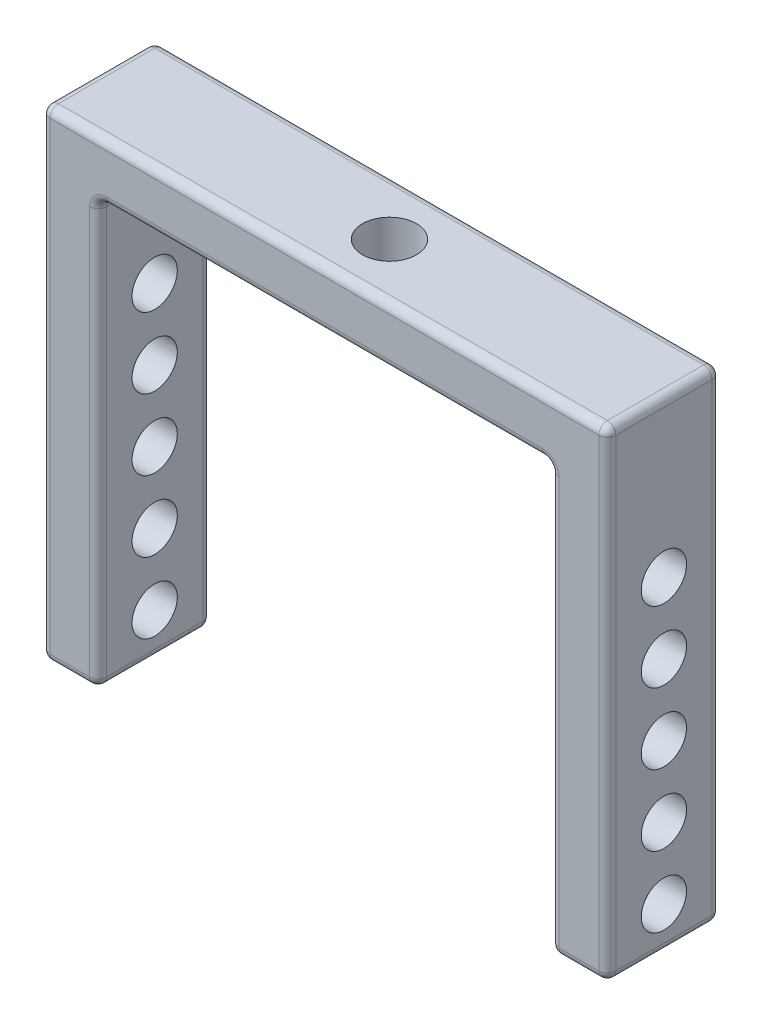
SolidWorks part; units mm, degrees
ref_plane "Alzado" through (0, 0, 0) normal (0, 0, 1) x (1, 0, 0)
ref_plane "Planta" through (0, 0, 0) normal (0, 1, 0) x (1, 0, 0)
ref_plane "Vista lateral" through (0, 0, 0) normal (1, 0, 0) x (0, 0, -1)
sketch "Sketch1" plane through (0, 0, 0) normal (0, 0, 1) x (1, 0, 0)
  line L0 (0, 0) -> (415, 0) construction
  line L1 (415, 0) -> (415, 270) construction
  line L2 (415, 270) -> (0, 270) construction
  line L3 (0, 270) -> (0, 0) construction
  line L4 (207.5, 270) -> (207.5, 0) construction
  line L6 (107.5, 210) -> (107.5, 60)
  line L7 (107.5, 60) -> (127.5, 60)
  line L8 (127.5, 210) -> (127.5, 60)
  line L9 (307.5, 230) -> (307.5, 210)
  line L10 (287.5, 210) -> (287.5, 60)
  line L11 (307.5, 230) -> (107.5, 230)
  line L12 (207.5, 230) -> (207.5, 210)
  line L13 (287.5, 210) -> (127.5, 210)
  line L14 (107.5, 230) -> (107.5, 210)
  line L15 (307.5, 60) -> (287.5, 60)
  line L16 (307.5, 210) -> (307.5, 60)
  point P3 (117.5, 135)
  point P13 (127.5, 135)
  point P14 (157.5, 220)
  dimension "D1" = 415
  dimension "D2" = 270
  dimension "D3" = 20
  dimension "D4" = 150
  dimension "D5" = 287.5
  dimension "D6" = 20
  dimension "D7" = 100
  dimension "D8" = 60
extrude "Boss-Extrude1" add sketch "Sketch1" along normal blind 40 contours L9 L16 L15 L10 L13 L8 L7 L6 L14 L11
fillet "Fillet1" radius 3 24 edges at (287.5, 210, 20) (127.5, 210, 20) (127.5, 135, 40) (207.5, 210, 40) (207.5, 230, 40) (207.5, 230, 0) (307.5, 145, 40) (307.5, 145, 0) (307.5, 60, 20) (297.5, 60, 40) (297.5, 60, 0) (287.5, 60, 20) (287.5, 135, 40) (287.5, 135, 0) (207.5, 210, 0) (127.5, 135, 0) (107.5, 145, 40) (107.5, 145, 0) (117.5, 60, 0) (107.5, 60, 20) (117.5, 60, 40) (127.5, 60, 20) (307.5, 230, 20) (107.5, 230, 20)
sketch "Sketch2" plane through (0, 230, 0) normal (0, 1, 0) x (1, 0, 0)
  line L0 (110.5, -3) -> (110.5, -37) construction
  line L1 (110.5, 0) -> (304.5, 0) construction
  circle A0 centre (210.5, -20) radius 9.55
  point P5 (110.5, -20)
  dimension "D2" = 20
  dimension "D3" = 19.1
  dimension "D1" = 100
extrude "Cut-Extrude1" cut sketch "Sketch2" against normal blind 20
sketch "Sketch5" plane through (107.5, 0, 0) normal (-1, 0, 0) x (0, 0, 1)
  line L0 (37, 60) -> (3, 60) construction
  line L1 (40, 227) -> (40, 63) construction
  circle A0 centre (20, 75) radius 8
  dimension "D1" = 15
  dimension "D3" = 16
  dimension "D2" = 20
extrude "Cut-Extrude2" cut sketch "Sketch5" against normal blind 200
pattern_linear "LPattern2" count 5 spacing 25 along (0, 1, 0) of "Cut-Extrude2"
